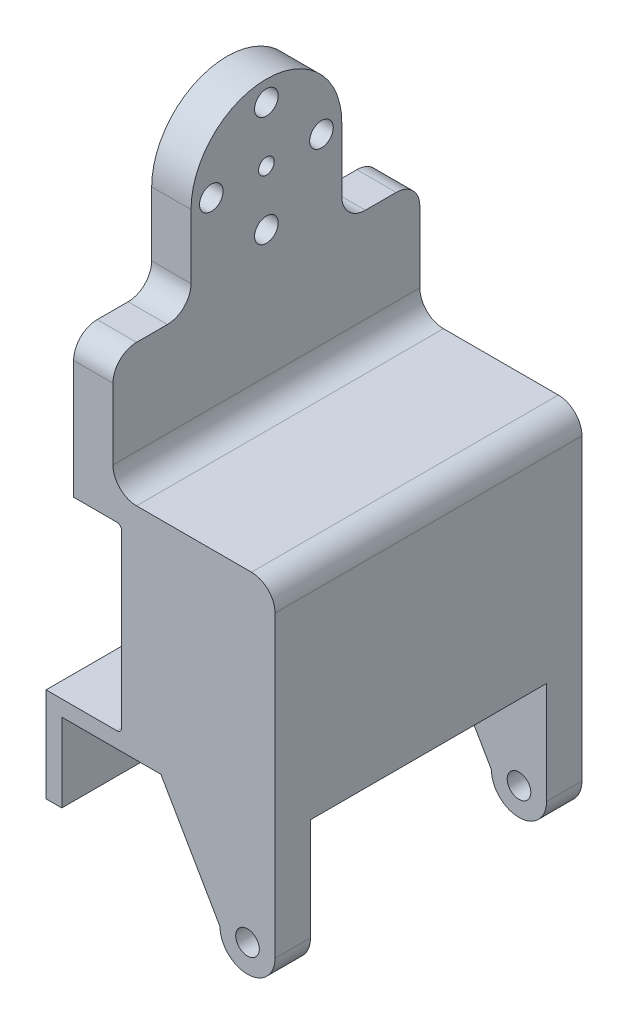
SolidWorks part; units mm, degrees
ref_plane "Front Plane" through (0, 0, 0) normal (0, 0, 1) x (1, 0, 0)
ref_plane "Top Plane" through (0, 0, 0) normal (0, 1, 0) x (1, 0, 0)
ref_plane "Right Plane" through (0, 0, 0) normal (1, 0, 0) x (0, 0, -1)
sketch "Sketch1" plane through (0, 0, 0) normal (0, 0, 1) x (1, 0, 0)
  line L0 (-18.428, 26) -> (-18.428, 0)
  line L1 (23.9404, 0) -> (-23.9404, 0) construction
  line L2 (-18.428, 0) -> (-43.528, 0)
  line L3 (-43.528, 0) -> (-43.528, -2)
  line L4 (-43.528, -2) -> (-14.428, -2)
  line L5 (-18.428, 26) -> (-14.428, 26)
  line L6 (-14.428, 26) -> (-14.428, -2)
  dimension "D1" = 25.1
  dimension "D2" = 4
  dimension "D3" = 28
  dimension "D4" = 2
extrude "Boss-Extrude1" add sketch "Sketch1" along normal mid plane 39
sketch "Sketch2" plane through (0, 0, 0) normal (1, 0, 0) x (0, 0, -1)
  line L0 (0, 23.9404) -> (0, -23.9404) construction
  line L1 (-19.5, 26) -> (19.5, 26) construction
  line L5 (0.5983, 34.4274) -> (0.2652, 34.184)
  line L6 (0.5983, 34.4274) -> (0.7801, 34.057)
  line L7 (-3.6245, 14.7948) -> (-4.0062, 14.6382)
  line L8 (-3.6245, 14.7948) -> (-3.5366, 14.3917)
  line L9 (-12.423, -3.2567) -> (-12.831, -3.3174)
  line L10 (-12.423, -3.2567) -> (-12.434, -3.6691)
  line L11 (-25.2858, -18.678) -> (-25.6965, -18.6393)
  line L12 (-25.2858, -18.678) -> (-25.3952, -19.0758)
  line L13 (-41.4654, -30.573) -> (-41.8549, -30.4371)
  line L14 (-41.4654, -30.573) -> (-41.6668, -30.933)
  line L15 (-60.0215, -38.2502) -> (-60.3672, -38.0251)
  line L16 (-60.0215, -38.2502) -> (-60.3032, -38.5516)
  line L17 (-79.8756, -41.2636) -> (-80.1574, -40.9623)
  line L18 (-79.8756, -41.2636) -> (-80.2213, -41.4888)
  line L19 (-99.874, -39.4381) -> (-100.0755, -39.078)
  line L20 (-99.874, -39.4381) -> (-100.2636, -39.574)
  line L21 (-118.8545, -32.8796) -> (-118.9639, -32.4818)
  line L22 (-118.8545, -32.8796) -> (-119.2652, -32.9183)
  line L23 (-135.7138, -21.9694) -> (-135.7249, -21.557)
  line L24 (-135.7138, -21.9694) -> (-136.1219, -21.9087)
  line L25 (-149.4722, -7.3416) -> (-149.3843, -6.9385)
  line L26 (-149.4722, -7.3416) -> (-149.8539, -7.185)
  line L27 (-159.3302, 10.1538) -> (-159.1484, 10.5241)
  line L28 (-159.3302, 10.1538) -> (-159.6633, 10.3972)
  line L29 (-164.7148, 29.5) -> (-164.4496, 29.816)
  line L30 (-164.7148, 29.5) -> (-164.98, 29.816)
  line L31 (-165.3131, 49.5726) -> (-164.98, 49.816)
  line L32 (-165.3131, 49.5726) -> (-165.495, 49.943)
  line L33 (-161.0903, 69.2052) -> (-160.7086, 69.3618)
  line L34 (-161.0903, 69.2052) -> (-161.1783, 69.6083)
  line L35 (-152.2918, 87.2567) -> (-151.8838, 87.3174)
  line L36 (-152.2918, 87.2567) -> (-152.2808, 87.6691)
  line L37 (-139.429, 102.678) -> (-139.0183, 102.6393)
  line L38 (-139.429, 102.678) -> (-139.3196, 103.0758)
  line L39 (-123.2495, 114.573) -> (-122.8599, 114.4371)
  line L40 (-123.2495, 114.573) -> (-123.048, 114.933)
  line L41 (-104.6934, 122.2502) -> (-104.3477, 122.0251)
  line L42 (-104.6934, 122.2502) -> (-104.4116, 122.5516)
  line L43 (-84.8392, 125.2636) -> (-84.5574, 124.9623)
  line L44 (-84.8392, 125.2636) -> (-84.4935, 125.4888)
  line L45 (-64.8408, 123.4381) -> (-64.6393, 123.078)
  line L46 (-64.8408, 123.4381) -> (-64.4512, 123.574)
  line L47 (-45.8604, 116.8796) -> (-45.7509, 116.4818)
  line L48 (-45.8604, 116.8796) -> (-45.4496, 116.9183)
  line L49 (-29.001, 105.9694) -> (-28.99, 105.557)
  line L50 (-29.001, 105.9694) -> (-28.593, 105.9087)
  line L51 (-15.2426, 91.3416) -> (-15.3305, 90.9385)
  line L52 (-15.2426, 91.3416) -> (-14.8609, 91.185)
  line L53 (-5.3846, 73.8462) -> (-5.5665, 73.4759)
  line L54 (-5.3846, 73.8462) -> (-5.0515, 73.6028)
  circle A0 centre (0, 20) radius 2.2
  dimension "D1" = 4.4
  dimension "D2" = 6
ref_plane "Plane1" through (0, -2, 0) normal (0, 1, 0) x (1, 0, 0)
sketch "Sketch3" plane through (0, -2, 0) normal (0, 1, 0) x (1, 0, 0)
  line L0 (-43.528, 19.5) -> (-14.428, 19.5) construction
  line L1 (-43.528, -19.5) -> (-41.528, -19.5)
  line L2 (-43.528, -19.5) -> (-43.528, 19.5)
  line L3 (-43.528, 19.5) -> (-41.528, 19.5)
  line L4 (-41.528, -19.5) -> (-41.528, 19.5)
  dimension "D1" = 2
extrude "Boss-Extrude2" add sketch "Sketch3" against normal blind 10
sketch "Sketch4" plane through (-41.528, 0, 0) normal (1, 0, 0) x (0, 0, -1)
  line L0 (0, 23.9404) -> (0, -23.9404) construction
  line L1 (-19.5, -12) -> (19.5, -12) construction
  circle A0 centre (0, -7) radius 2.5
  dimension "D1" = 5
  dimension "D2" = 5
extrude "Cut-Extrude3" cut sketch "Sketch4" against normal blind 10
sketch "Sketch5" plane through (-18.428, 0, 0) normal (-1, 0, 0) x (0, 0, 1)
  line L0 (23.9404, 0) -> (-23.9404, 0) construction
  line L1 (-19.5, 0) -> (-14.4, 0)
  line L2 (-19.5, 0) -> (-19.5, 22.95)
  line L3 (-19.5, 22.95) -> (-14.4, 22.95)
  line L4 (-14.4, 0) -> (-14.4, 22.95)
  line L5 (-19.5, 0) -> (-19.5, -12) construction
  dimension "D1" = 22.95
  dimension "D2" = 5.1
extrude "Boss-Extrude3" add sketch "Sketch5" along normal up to surface (25.1 mm away) up to face at (-43.528, -7, -2.5)
sketch "Sketch8" plane through (0, 0, -14.4) normal (0, 0, 1) x (1, 0, 0)
  line L0 (23.9404, 0) -> (-23.9404, 0) construction
  line L1 (-18.428, 0) -> (-33.928, 0)
  line L2 (-18.428, 0) -> (-18.428, 22.95)
  line L3 (-18.428, 22.95) -> (-33.928, 22.95)
  line L4 (-33.928, 0) -> (-33.928, 22.95)
  line L5 (-18.428, 0) -> (-18.428, 22.95) construction
  line L6 (-43.528, 22.95) -> (-18.428, 22.95) construction
  dimension "D1" = 15.5
extrude "Boss-Extrude4" add sketch "Sketch8" along normal up to surface (33.9 mm away) up to face at (-29.478, 3, 19.5)
sketch "Sketch11" plane through (0, 0, 0) normal (0, 0, 1) x (1, 0, 0)
  line L0 (-14.428, -2) -> (-14.428, -15)
  line L1 (17.6962, -2) -> (-17.6962, -2) construction
  line L2 (-14.428, -2) -> (-14.428, 26) construction
  line L3 (-21.428, -15) -> (-28.9335, -2)
  line L4 (-28.9335, -2) -> (-14.428, -2)
  arc A0 (-21.428, -15) -> (-14.428, -15) centre (-17.928, -15) ccw
  dimension "D1" = 7
  dimension "12" = 13
  dimension "D2" = 60
extrude "Boss-Extrude5" add sketch "Sketch11" along normal mid plane 39
ref_plane "Plane2" through (0, -18.5, 0) normal (0, 1, 0) x (1, 0, 0)
sketch "Sketch12" plane through (0, -18.5, 0) normal (0, 1, 0) x (1, 0, 0)
  line L0 (-23.9404, 0) -> (23.9404, 0) construction
  line L1 (-3.8335, -15) -> (-34.0971, -15)
  line L2 (-3.8335, -15) -> (-3.8335, 15)
  line L3 (-3.8335, 15) -> (-34.0971, 15)
  line L4 (-34.0971, -15) -> (-34.0971, 15)
  line L5 (-3.8335, -15) -> (-34.0971, 15) construction
  line L6 (-3.8335, 15) -> (-34.0971, -15) construction
  point P0 (-18.9653, 0)
  dimension "D1" = 30
extrude "Cut-Extrude6" cut sketch "Sketch12" along normal up to surface (16.5 mm away) up to face at (-35.2307, -2, 0)
sketch "Sketch13" plane through (0, 0, 19.5) normal (0, 0, 1) x (1, 0, 0)
  line L0 (-21.428, -15) -> (-14.428, -15) construction
  circle A0 centre (-17.928, -15) radius 1.5
  dimension "D1" = 3
extrude "Cut-Extrude7" cut sketch "Sketch13" against normal through all
fillet "Fillet3" radius 3 1 edges at (-14.428, 26, 0)
sketch "Sketch16" plane through (-18.428, 0, 0) normal (-1, 0, 0) x (0, 0, 1)
  line L1 (-19.5, 26) -> (19.5, 26)
  line L2 (-19.5, 26) -> (-19.5, 22.95)
  line L3 (-19.5, 22.95) -> (19.5, 22.95)
  line L4 (19.5, 26) -> (19.5, 22.95)
extrude "Boss-Extrude6" add sketch "Sketch16" along normal up to surface (25.1 mm away) up to face at (-43.528, -7, -2.5)
sketch "Sketch17" plane through (0, 26, 0) normal (0, 1, 0) x (1, 0, 0)
  line L1 (-40.028, 19.5) -> (-35.028, 19.5)
  line L2 (-40.028, 19.5) -> (-40.028, -19.5)
  line L3 (-40.028, -19.5) -> (-35.028, -19.5)
  line L4 (-35.028, 19.5) -> (-35.028, -19.5)
  line L5 (-43.528, 19.5) -> (-43.528, -19.5) construction
  dimension "D1" = 5
  dimension "D2" = 3.5
extrude "Boss-Extrude7" add sketch "Sketch17" along normal blind 15
fillet "Fillet4" radius 3 1 edges at (-35.028, 26, 0)
sketch "Sketch18" plane through (0, 41, 0) normal (0, 1, 0) x (1, 0, 0)
  line L0 (-40.028, 19.5) -> (-40.028, -19.5) construction
  line L1 (-40.028, 9.58) -> (-35.028, 9.58)
  line L2 (-40.028, 9.58) -> (-40.028, -9.58)
  line L3 (-40.028, -9.58) -> (-35.028, -9.58)
  line L4 (-35.028, 9.58) -> (-35.028, -9.58)
  line L5 (-35.028, -19.5) -> (-35.028, 19.5) construction
  line L6 (-35.028, 19.5) -> (-40.028, 19.5) construction
  dimension "D1" = 19.16
  dimension "D2" = 9.92
fillet "Fillet11" radius 0.6 1 edges at (-33.928, 22.95, 2.55)
fillet "Fillet12" radius 0.6 1 edges at (-33.928, 0, 2.55)
sketch "Sketch20" plane through (-35.028, 0, 0) normal (1, 0, 0) x (0, 0, -1)
  line L0 (-19.5, 22.95) -> (14.4, 22.95) construction
  line L1 (0, 23.9404) -> (0, -23.9404) construction
  line L2 (-13.513, 52.15) -> (16.5191, 52.15)
  arc A0 (0, 46.65) -> (0, 43.65) centre (0, 45.15) ccw
  arc A1 (0, 61.725) -> (-9.575, 52.15) centre (0, 52.15) ccw
  arc A2 (9.575, 52.15) -> (0, 61.725) centre (0, 52.15) ccw
  arc A3 (0, 43.65) -> (0, 46.65) centre (0, 45.15) ccw
  arc A4 (-7, 53.65) -> (-7, 50.65) centre (-7, 52.15) ccw
  arc A5 (-5.5, 52.15) -> (-7, 53.65) centre (-7, 52.15) ccw
  arc A6 (-7, 50.65) -> (-5.5, 52.15) centre (-7, 52.15) ccw
  arc A7 (0, 60.65) -> (0, 57.65) centre (0, 59.15) ccw
  arc A8 (0, 57.65) -> (0, 60.65) centre (0, 59.15) ccw
  arc A9 (7, 53.65) -> (5.5, 52.1518) centre (7, 52.15) ccw
  arc A10 (7, 50.65) -> (7, 53.65) centre (7, 52.15) ccw
  arc A11 (5.5, 52.1518) -> (7, 50.65) centre (7, 52.15) ccw
  arc A12 (1, 52.15) -> (-1, 52.15) centre (0, 52.15) ccw
  arc A13 (-1, 52.15) -> (1, 52.15) centre (0, 52.15) ccw
  dimension "D5" = 0
  dimension "D9" = 7
  dimension "D3" = 9.575
  dimension "D1" = 0
  dimension "D2" = 7
  dimension "D6" = 7
  dimension "D8" = 7
  dimension "D11" = 29.2
extrude "Boss-Extrude12" add sketch "Sketch18" along normal blind 25.725
extrude "Cut-Extrude13" cut sketch "Sketch20" against normal through all both and the other way through all contours A10 A9 A11 | A13 A12 | A3 A0 | A6 A5 A4 | A8 A7
sketch "Sketch21" plane through (-35.028, 0, 0) normal (1, 0, 0) x (0, 0, -1)
  line L5 (9.58, 66.725) -> (9.58, 41) construction
  line L6 (-9.58, 66.725) -> (9.58, 66.725)
  line L7 (-9.58, 66.725) -> (-9.58, 52.15)
  line L9 (9.58, 66.725) -> (9.58, 52.15)
  arc A3 (9.58, 52.15) -> (-9.58, 52.15) centre (0, 52.15) ccw
  dimension "D1" = 19.16
extrude "Cut-Extrude14" cut sketch "Sketch21" against normal through all
fillet "Fillet15" radius 3 1 edges at (-37.528, 41, 9.58)
fillet "Fillet16" radius 3 1 edges at (-37.528, 41, 19.5)
fillet "Fillet17" radius 3 1 edges at (-37.528, 41, -19.5)
fillet "Fillet18" radius 3 1 edges at (-37.528, 41, -9.58)
sketch "Sketch23" plane through (0, 26, 0) normal (0, 1, 0) x (1, 0, 0)
  line L1 (-40.028, 19.5) -> (-43.528, 19.5)
  line L2 (-40.028, 19.5) -> (-40.028, -19.5)
  line L3 (-40.028, -19.5) -> (-43.528, -19.5)
  line L4 (-43.528, 19.5) -> (-43.528, -19.5)
extrude "Cut-Extrude15" cut sketch "Sketch23" against normal blind 26
